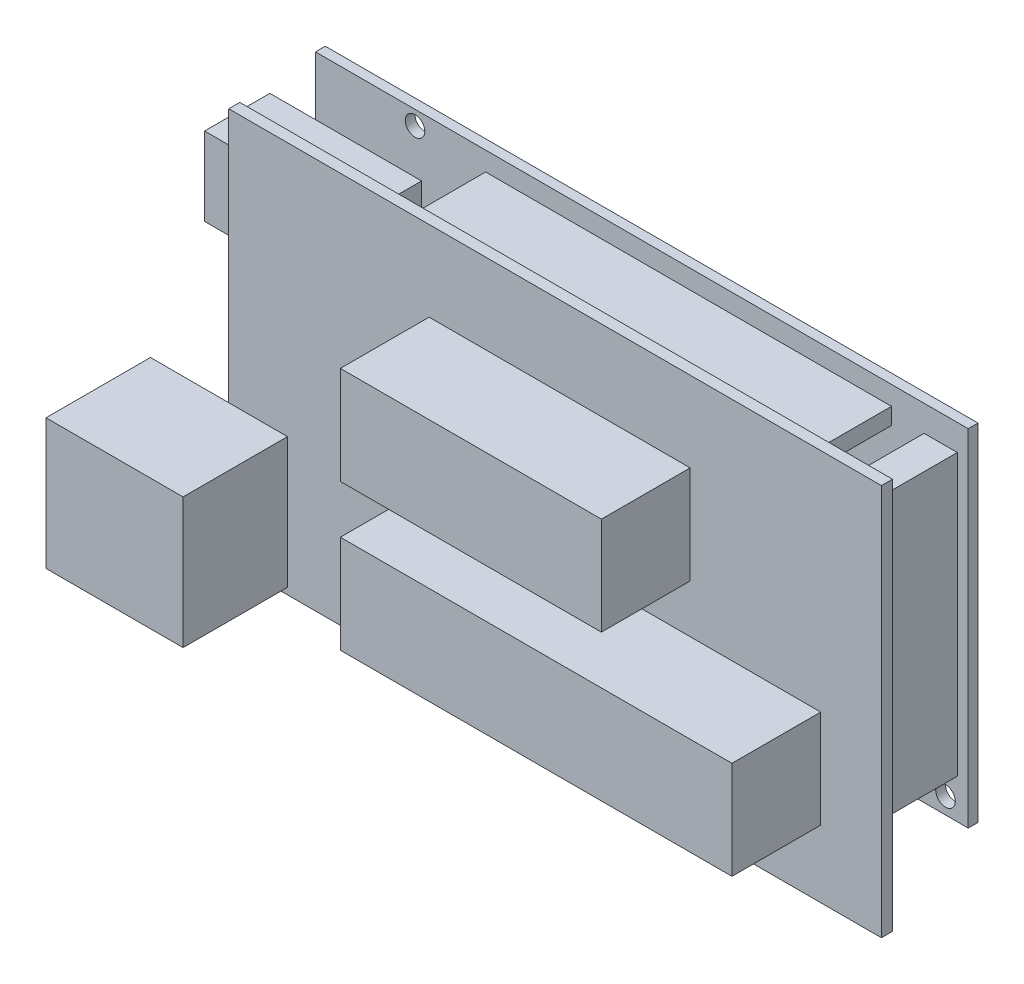
SolidWorks part; units mm, degrees
ref_plane "Plano frontal" through (0, 0, 0) normal (0, 0, 1) x (1, 0, 0)
ref_plane "Plano superior" through (0, 0, 0) normal (0, 1, 0) x (1, 0, 0)
ref_plane "Plano direito" through (0, 0, 0) normal (1, 0, 0) x (0, 0, -1)
sketch "Esboço1" plane through (0, 0, 0) normal (0, 0, 1) x (1, 0, 0)
  line L1 (-50, 30) -> (50, 30)
  line L2 (-50, 30) -> (-50, -30)
  line L3 (-50, -30) -> (50, -30)
  line L4 (50, 30) -> (50, -30)
  line L5 (-50, 30) -> (50, -30) construction
  line L6 (-50, -30) -> (50, 30) construction
  point P0 (0, 0)
  dimension "D1" = 60
  dimension "D2" = 100
extrude "Ressalto-extrusão1" add sketch "Esboço1" along normal blind 1.7
sketch "Esboço2" plane through (0, 0, 1.7) normal (0, 0, 1) x (1, 0, 0)
  line L0 (-50, -30) -> (50, -30) construction
  line L1 (-19.3, -4.7) -> (40.7, -4.7)
  line L2 (-19.3, -4.7) -> (-19.3, -19.7)
  line L3 (-19.3, -19.7) -> (40.7, -19.7)
  line L4 (40.7, -4.7) -> (40.7, -19.7)
  line L5 (50, -30) -> (50, 30) construction
  line L7 (-19.3, 2.7) -> (20.7, 2.7)
  line L8 (-19.3, 2.7) -> (-19.3, 17.7)
  line L9 (-19.3, 17.7) -> (20.7, 17.7)
  line L10 (20.7, 2.7) -> (20.7, 17.7)
  dimension "D1" = 60
  dimension "D2" = 15
  dimension "D3" = 10.3
  dimension "D4" = 9.3
  dimension "D5" = 40
  dimension "D6" = 7.4
extrude "Ressalto-extrusão2" add sketch "Esboço2" along normal blind 13.6
sketch "Esboço3" plane through (0, 0, 0) normal (0, 0, -1) x (-1, 0, 0)
  line L0 (50, -30) -> (-50, -30) construction
  line L1 (50, 30.9) -> (-50, 30.9)
  line L2 (50, 30.9) -> (50, -22.1)
  line L3 (50, -22.1) -> (-50, -22.1)
  line L4 (-50, 30.9) -> (-50, -22.1)
  line L5 (50, 30) -> (50, -30) construction
  line L6 (-50, -30) -> (-50, 30) construction
  dimension "D1" = 7.9
  dimension "D2" = 53
extrude "Ressalto-extrusão6" add sketch "Esboço3" along normal blind 1.5 from offset 11.6 separate body
sketch "Esboço4" plane through (0, 0, -11.6) normal (0, 0, 1) x (1, 0, 0)
  line L1 (-23.9415, 27.9898) -> (38.2426, 27.9898)
  line L2 (-23.9415, 27.9898) -> (-23.9415, 25.4498)
  line L3 (-23.9415, 25.4498) -> (38.2426, 25.4498)
  line L4 (38.2426, 27.9898) -> (38.2426, 25.4498)
  line L5 (48.3249, 26.9052) -> (43.2449, 26.9052)
  line L6 (48.3249, 26.9052) -> (48.3249, -16.0526)
  line L7 (48.3249, -16.0526) -> (43.2449, -16.0526)
  line L8 (43.2449, 26.9052) -> (43.2449, -16.0526)
  line L9 (38.2426, -19.9599) -> (-17.8292, -19.9599)
  line L10 (38.2426, -19.9599) -> (38.2426, -17.4199)
  line L11 (38.2426, -17.4199) -> (-17.8292, -17.4199)
  line L12 (-17.8292, -19.9599) -> (-17.8292, -17.4199)
  dimension "D1" = 2.54
  dimension "D2" = 5.08
extrude "Ressalto-extrusão8" add sketch "Esboço4" along normal up to surface (11.6 mm away) up to face at (0, 0, 0)
sketch "Esboço6" plane through (0, 0, 1.7) normal (0, 0, 1) x (1, 0, 0)
  line L0 (-50, -30) -> (50, -30) construction
  line L1 (-62, -9) -> (-41, -9)
  line L2 (-62, -9) -> (-62, -29)
  line L3 (-62, -29) -> (-41, -29)
  line L4 (-41, -9) -> (-41, -29)
  line L5 (-50, 30) -> (-50, -30) construction
  dimension "D1" = 20
  dimension "D2" = 1
  dimension "D3" = 12
  dimension "D4" = 21
extrude "Ressalto-extrusão9" add sketch "Esboço6" along normal blind 16
sketch "Esboço7" plane through (0, 0, -11.6) normal (0, 0, 1) x (1, 0, 0)
  line L0 (-50, 30.9) -> (50, 30.9) construction
  line L1 (-33.753, 21.9) -> (-57, 21.9)
  line L2 (-33.753, 21.9) -> (-33.753, 9.9)
  line L3 (-33.753, 9.9) -> (-57, 9.9)
  line L4 (-57, 21.9) -> (-57, 9.9)
  line L5 (-50, -22.1) -> (-50, 30.9) construction
  dimension "D1" = 9
  dimension "D2" = 12
  dimension "D3" = 7
extrude "Ressalto-extrusão10" add sketch "Esboço7" along normal blind 10
sketch "Esboço8" plane through (0, 0, -13.1) normal (0, 0, -1) x (-1, 0, 0)
  line L0 (50, -22.1) -> (50, 30.9) construction
  line L1 (-50, -22.1) -> (50, -22.1) construction
  circle A0 centre (34.76, 28.7) radius 1.5
  circle A1 centre (36.03, -19.56) radius 1.5
  circle A2 centre (-46.52, -19.56) radius 1.5
  dimension "D1" = 3
  dimension "D2" = 15.24
  dimension "D3" = 13.97
  dimension "D4" = 96.52
  dimension "D5" = 2.54
  dimension "D6" = 2.54
  dimension "D7" = 50.8
extrude "Corte-extrusão1" cut sketch "Esboço8" against normal blind 10
equation "\"D5@Esboço2\"=\"D1@Esboço2\"*2/3"
equation "\"D2@Esboço4\"=\"D1@Esboço4\"*2"
